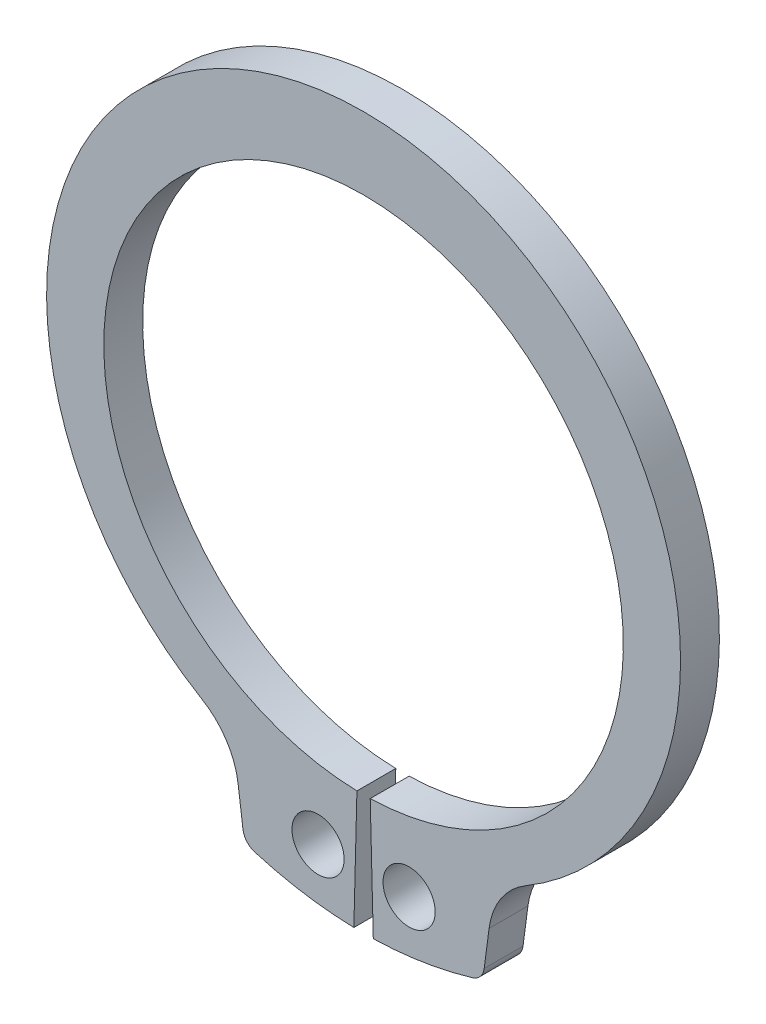
SolidWorks part; units mm, degrees
ref_plane "Front Plane" through (0, 0, 0) normal (0, 0, 1) x (1, 0, 0)
ref_plane "Top Plane" through (0, 0, 0) normal (0, 1, 0) x (1, 0, 0)
ref_plane "Right Plane" through (0, 0, 0) normal (1, 0, 0) x (0, 0, -1)
other "PropertyManager"
sketch "Clipboard" plane through (0, 0, 0) normal (0, 0, 1) x (1, 0, 0)
  line L0 (0, 0) -> (1.651, 0)
  line L1 (0, 0) -> (0, 1.016)
  line L2 (0, 0) -> (0, -2.7432)
  circle A0 centre (0, 0) radius 0.5969
  circle A1 centre (0, 0) radius 6.35
  dimension "HoleDia" = 1.1938
  dimension "ShaftDia" = 12.7
  dimension "LargeSection" = 1.651
  dimension "SmallSection" = 1.016
  dimension "LugSection" = 2.7432
sketch "BodySketch" plane through (0, 0, 0) normal (0, 0, 1) x (1, 0, 0)
  line L0 (-1.5431, 0) -> (1.5431, 0) construction
  line L1 (0, 0) -> (0, 7.5946) construction
  line L2 (0.1521, -5.9417) -> (0.2223, -8.684)
  line L3 (-0.1521, -5.9417) -> (-0.2223, -8.684)
  line L4 (0, 0) -> (4.5837, -7.3791) construction
  line L5 (0, 0) -> (-4.5837, -7.3791) construction
  line L7 (2.8717, -7.1537) -> (2.7594, -8.0068)
  line L8 (-2.8717, -7.1537) -> (-2.7594, -8.0068)
  circle A0 centre (0, 0) radius 5.9436 construction
  arc A1 (0.1521, -5.9417) -> (-0.1521, -5.9417) centre (0, 0) ccw
  arc A2 (3.6723, -5.9119) -> (-3.6723, -5.9119) centre (0, 0.3421) ccw construction
  arc A3 (0.2223, -8.684) -> (2.4909, -8.322) centre (0, 0) ccw
  arc A4 (3.7022, -5.8942) -> (2.8717, -7.1537) centre (4.5837, -7.3791) ccw
  arc A5 (-2.8717, -7.1537) -> (-3.7022, -5.8942) centre (-4.5837, -7.3791) ccw
  arc A6 (-2.4909, -8.322) -> (-0.2223, -8.684) centre (0, 0) ccw
  arc A7 (3.7022, -5.8942) -> (-3.7022, -5.8942) centre (0, 0.3421) ccw
  arc A8 (-2.9003, -6.9365) -> (2.9003, -6.9365) centre (0, 0) ccw construction
  circle A9 centre (1.0414, -7.4459) radius 0.5969
  circle A10 centre (-1.0414, -7.4459) radius 0.5969
  arc A11 (2.7594, -8.0068) -> (2.4909, -8.322) centre (2.3816, -7.957) cw
  arc A12 (-2.7594, -8.0068) -> (-2.4909, -8.322) centre (-2.3816, -7.957) ccw
  point P28 (2.7277, -8.2474)
  point P31 (-2.7277, -8.2474)
  dimension "GrooveDia" = 11.8872
  dimension "LugRad" = 8.6868
  dimension "HoleOffsetRad" = 7.5184
  dimension "HoleDia" = 1.1938
  dimension "D3" = 0.381
  dimension "LargeRad" = 7.5946
  dimension "SmallRad" = 6.9596
  dimension "SmallAngle" = 63.695
  dimension "D2" = 15
  dimension "HoleSpacing" = 2.0828
  dimension "Gap" = 0.4445
extrude "Body" add sketch "BodySketch" along normal blind 0.889
sketch "NotchSketch" plane through (0, 0, 0) normal (0, 0, 1) x (1, 0, 0)
  line L0 (1.0414, -6.849) -> (1.0414, -8.0428)
  line L1 (1.0414, -8.0428) -> (-1.0414, -8.0428)
  line L2 (-1.0414, -8.0428) -> (-1.0414, -6.849)
  line L3 (-1.0414, -6.849) -> (1.0414, -6.849)
  circle A1 centre (1.0414, -7.4459) radius 0.5969 construction
  circle A2 centre (-1.0414, -7.4459) radius 0.5969 construction
extrude "Notch" [suppressed] cut sketch "NotchSketch" along normal up to next
other "Freeze***"
equation "' \"ShaftDia@Clipboard\" = 0.125"
equation "' \"Thickness@Body\" = 0.01"
equation "' \"GrooveDia@BodySke\" = 0.117"
equation "' \"LugSection@Clipboard\" = 0.046"
equation "' \"LargeSection@Clipboard\" = 0.018"
equation "' \"SmallSection@Clipboard\" = 0.011"
equation "' \"HoleDia@Clipboard\" = 0.026"
equation "' \"ShaftDia@Clipboard\" = 0.394"
equation "' \"Thickness@Body\" = 0.025"
equation "' \"GrooveDia@BodySke\" = 0.369"
equation "' \"LugSection@Clipboard\" = 0.087"
equation "' \"LargeSection@Clipboard\" = 0.052"
equation "' \"SmallSection@Clipboard\" = 0.031"
equation "' \"HoleDia@Clipboard\" = 0.041"
equation "\"Gap@BodySketch\" =  \"Thickness@Body\" / 2"
equation "\"LargeRad@BodySketch\" =  \"GrooveDia@BodySketch\" / 2 +  \"LargeSection@Clipboard\""
equation "\"SmallRad@BodySketch\" =  \"GrooveDia@BodySketch\" / 2 +  \"SmallSection@Clipboard\""
equation "\"LugRad@BodySketch\" = \"GrooveDia@BodySketch\" / 2 + \"LugSection@Clipboard\""
equation "\"HoleOffsetRad@BodySketch\" = (  \"ShaftDia@Clipboard\" / 2 + \"LugRad@BodySketch\" ) / 2"
equation "\"HoleSpacing@BodySketch\" = \"Gap@BodySketch\"  * 2 +  \"HoleDia@Clipboard\""
equation "\"HoleDia@BodySketch\" =  \"HoleDia@Clipboard\""
equation "\"SmallAngle@BodySketch\" = atn(\"HoleSpacing@BodySketch\" / 2 / sqr(\"HoleOffsetRad@BodySketch\"  * \"HoleOffsetRad@BodySketch\" - (\"HoleSpacing@BodySketch\" / 2) * (\"HoleSpacing@BodySketch\" / 2) ))  * 8 * ( 180 / 3.141593)"
